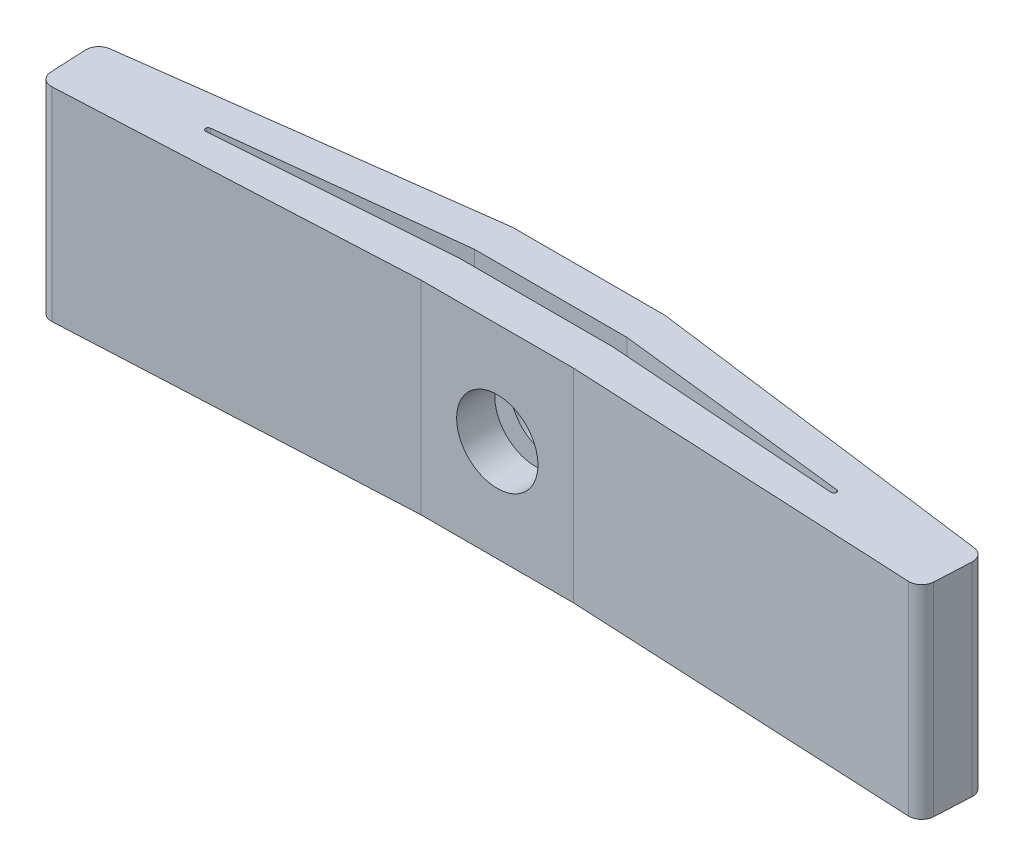
SolidWorks part; units mm, degrees
ref_plane "Front" through (0, 0, 0) normal (0, 0, 1) x (1, 0, 0)
ref_plane "Top" through (0, 0, 0) normal (0, 1, 0) x (1, 0, 0)
ref_plane "Right" through (0, 0, 0) normal (1, 0, 0) x (0, 0, -1)
sketch "Sketch1" plane through (0, 0, 0) normal (0, 1, 0) x (1, 0, 0)
  line L0 (0, 0) -> (34.7, 0) construction
  line L1 (17.35, 0) -> (17.35, 17.8266) construction
  line L2 (20.35, 0.7) -> (14.35, 0.7)
  line L3 (14.35, 0.7) -> (0, 0)
  line L4 (0, 0) -> (-0.1171, 2.4)
  line L5 (20.35, 2.2) -> (14.35, 2.2)
  line L6 (14.35, 2.2) -> (0.35, 1.2)
  line L7 (0.35, 1.2) -> (14.35, 2.8)
  line L8 (14.35, 2.8) -> (20.35, 2.8)
  line L9 (20.35, 4.3) -> (34.8171, 2.4)
  line L10 (20.35, 4.3) -> (14.35, 4.3)
  line L11 (14.35, 4.3) -> (-0.1171, 2.4)
  line L12 (34.35, 1.2) -> (20.35, 2.8)
  line L13 (20.35, 2.2) -> (34.35, 1.2)
  line L14 (34.7, 0) -> (34.8171, 2.4)
  line L15 (20.35, 0.7) -> (34.7, 0)
  line L16 (14.35, 4.3) -> (14.35, 0.7) construction
  point P25 (17.35, 4.3)
  point P26 (17.35, 2.8)
  point P28 (17.35, 2.2)
  point P29 (17.35, 0.7)
  dimension "D1" = 34.7
  dimension "D2" = 1.4
  dimension "D3" = 1.5
  dimension "D4" = 1.5
  dimension "D5" = 0.6
  dimension "D6" = 6
  dimension "D7" = 17
  dimension "D8" = 2.4
  dimension "D9" = 1.2
extrude "Boss-Extrude1" add sketch "Sketch1" along normal blind 8
fillet "Fillet1" radius 0.1 2 edges at (34.35, 4, -1.2) (0.35, 4, -1.2)
fillet "Fillet2" radius 0.5 4 edges at (-0.1171, 4, -2.4) (34.8171, 4, -2.4) (34.7, 4, 0) (0, 4, 0)
sketch "Sketch2" plane through (0, 0, -4.3) normal (0, 0, -1) x (-1, 0, 0)
  line L0 (-17.35, 4) -> (-17.35, 0) construction
  line L1 (-20.35, 0) -> (-14.35, 0) construction
  line L2 (-17.35, 4) -> (-17.35, 8) construction
  line L3 (-20.35, 8) -> (-14.35, 8) construction
  circle A0 centre (-17.35, 4) radius 1.6
  dimension "D1" = 3.2
extrude "Cut-Extrude1" cut sketch "Sketch2" against normal through all
sketch "Sketch3" plane through (0.9002, 0, -6.8544) normal (0.1302, 0, -0.9915) x (-0.9915, 0, -0.1302)
  line L0 (-33.7475, 1) -> (-19.6168, 1) construction
  line L1 (-33.7475, 8) -> (-33.7475, 0) construction
  line L2 (-19.6168, 8) -> (-19.6168, 0) construction
  line L4 (-33.7475, 0) -> (-19.6168, 0) construction
  text T0 "BCL" font "Century Gothic" height in points 20
  dimension "D1" = 1
extrude "Boss-Extrude2" [suppressed] add sketch "Sketch3" along normal blind 0.4
sketch "Sketch4" plane through (-0.3118, 0, -2.3744) normal (-0.1302, 0, -0.9915) x (-0.9915, 0, 0.1302)
  line L0 (-14.7877, 1) -> (-0.6571, 1) construction
  line L1 (-14.7877, 8) -> (-14.7877, 0) construction
  line L2 (-0.6571, 0) -> (-0.6571, 8) construction
  line L3 (-14.7877, 0) -> (-0.6571, 0) construction
  text T0 "02" font "Century Gothic" height in points 20
  dimension "D1" = 1
extrude "Boss-Extrude3" [suppressed] add sketch "Sketch4" along normal blind 0.4
sketch "Sketch5" plane through (-0.3118, 0, -2.3744) normal (-0.1302, 0, -0.9915) x (-0.9915, 0, 0.1302)
  line L0 (-14.7877, 1) -> (-0.6571, 1) construction
  line L1 (-14.7877, 8) -> (-14.7877, 0) construction
  line L2 (-0.6571, 0) -> (-0.6571, 8) construction
  line L3 (-14.7877, 0) -> (-0.6571, 0) construction
  text T0 ".."
  dimension "D1" = 1
extrude "revision indication" add sketch "Sketch5" along normal blind 0.4
